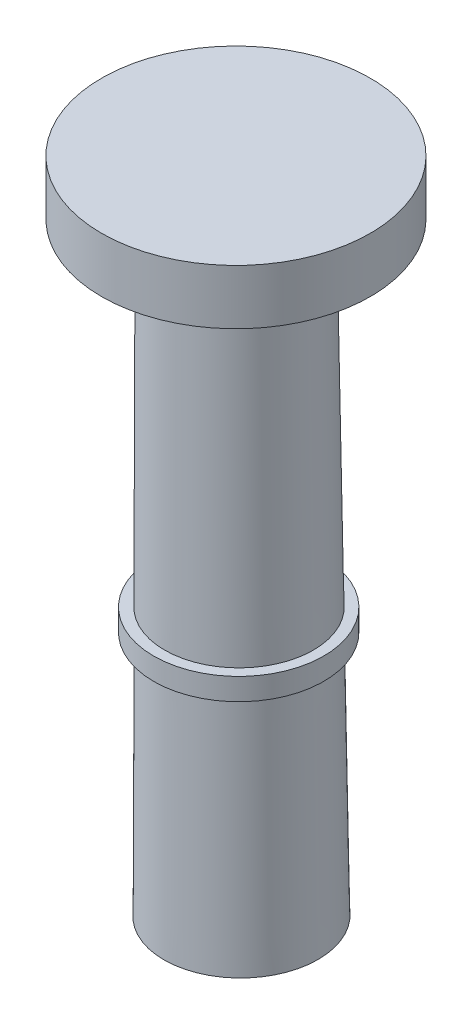
SolidWorks part; units mm, degrees
ref_plane "Front Plane" through (0, 0, 0) normal (0, 0, 1) x (1, 0, 0)
ref_plane "Top Plane" through (0, 0, 0) normal (0, 1, 0) x (1, 0, 0)
ref_plane "Right Plane" through (0, 0, 0) normal (1, 0, 0) x (0, 0, -1)
sketch "Sketch1" plane through (0, 0, 0) normal (0, 0, 1) x (1, 0, 0)
  line L0 (-50.9943, 48.8899) -> (-50.9943, -61.1101)
  line L1 (-50.9943, -61.1101) -> (-36.9943, -61.1101)
  line L2 (-50.9943, 48.8899) -> (-37.9943, 48.8899)
  line L3 (-37.9943, 48.8899) -> (-36.9943, -61.1101)
  dimension "D1" = 110
  dimension "D2" = 14
  dimension "D3" = 13
revolve "Revolve1" add sketch "Sketch1" angle 360 about L3
ref_plane "Plane2" through (0, 48.4713, 0) normal (0, 1, 0) x (1, 0, 0)
ref_plane "Plane3" through (0, 48.545, 0) normal (0, 1, 0) x (1, 0, 0)
sketch "Sketch3" plane through (0, 48.545, 0) normal (0, 1, 0) x (1, 0, 0)
  circle A0 centre (-37.9943, 0) radius 24.5
  dimension "D1" = 49
extrude "Boss-Extrude1" add sketch "Sketch3" along normal blind 10
ref_plane "Plane4" through (0, 58.545, 0) normal (0, 1, 0) x (1, 0, 0)
ref_plane "Plane5" through (0, -16.455, 0) normal (0, 1, 0) x (1, 0, 0)
sketch "Sketch4" plane through (0, -16.455, 0) normal (0, 1, 0) x (1, 0, 0)
  line L0 (-37.9943, 0) -> (-36.9943, 0) construction
  circle A0 centre (-37.4943, 0) radius 15.5
extrude "Boss-Extrude3" add sketch "Sketch4" along normal blind 4 contours A0
